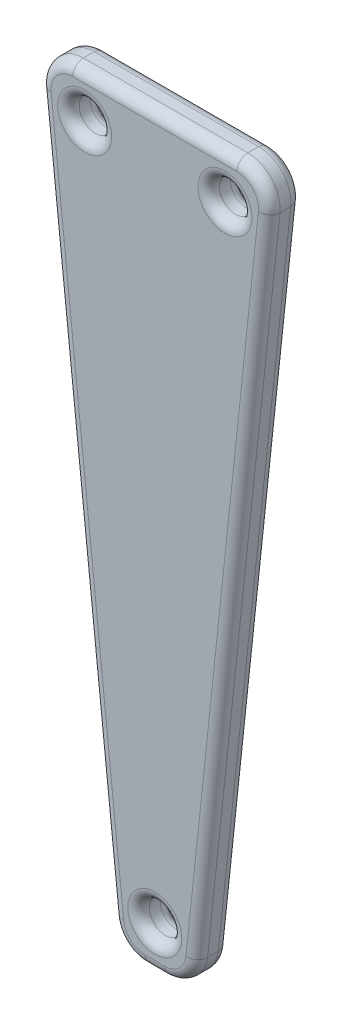
SolidWorks part; units mm, degrees
ref_plane "Front Plane" through (0, 0, 0) normal (0, 0, 1) x (1, 0, 0)
ref_plane "Top Plane" through (0, 0, 0) normal (0, 1, 0) x (1, 0, 0)
ref_plane "Right Plane" through (0, 0, 0) normal (1, 0, 0) x (0, 0, -1)
sketch "Sketch1" plane through (0, 0, 0) normal (0, 0, 1) x (1, 0, 0)
  line L0 (0, 0) -> (13, 0) construction
  line L1 (6.5, 0) -> (6.5, -61.08) construction
  line L2 (0, 0) -> (6.5, -61.08) construction
  line L3 (6.5, -61.08) -> (13, 0) construction
  line L4 (-4.0952, 0.6825) -> (2.6176, -62.3975)
  line L5 (10.3824, -62.3975) -> (17.0952, 0.6825)
  line L6 (-1.1121, 4) -> (14.1121, 4)
  line L7 (5.6008, -65.08) -> (7.3992, -65.08)
  line L8 (-4.4483, 4) -> (6.5, -98.8799) construction
  line L9 (6.5, -98.8799) -> (17.4483, 4) construction
  line L10 (-4.4483, 4) -> (17.4483, 4) construction
  circle A0 centre (0, 0) radius 1.5
  circle A1 centre (13, 0) radius 1.5
  circle A2 centre (6.5, -61.08) radius 1.5
  arc A3 (2.6176, -62.3975) -> (5.6008, -65.08) centre (5.6008, -62.08) ccw
  arc A4 (10.3824, -62.3975) -> (7.3992, -65.08) centre (7.3992, -62.08) cw
  arc A5 (17.0952, 0.6825) -> (14.1121, 4) centre (14.1121, 1) ccw
  arc A6 (-4.0952, 0.6825) -> (-1.1121, 4) centre (-1.1121, 1) cw
  dimension "D1" = 3
  dimension "D2" = 3
  dimension "D3" = 3
  dimension "D8" = 3
  dimension "D4" = 13
  dimension "D5" = 61.08
  dimension "D7" = 4
  dimension "D6" = 4
extrude "Boss-Extrude1" add sketch "Sketch1" along normal blind 3
fillet "Fillet1" radius 1 22 edges at (3.5948, -64.3107, 3) (3.5948, -64.3107, 0) (6.5, -65.08, 3) (6.5, -65.08, 0) (9.4052, -64.3107, 3) (9.4052, -64.3107, 0) (13.7388, -30.8575, 3) (13.7388, -30.8575, 0) (16.3428, 3.0059, 3) (16.3428, 3.0059, 0) (6.5, 4, 3) (6.5, 4, 0) (-3.3428, 3.0059, 3) (-3.3428, 3.0059, 0) (-0.7388, -30.8575, 3) (-0.7388, -30.8575, 0) (1.5, 0, 0) (1.5, 0, 3) (14.5, 0, 0) (14.5, 0, 3) (8, -61.08, 0) (8, -61.08, 3)
